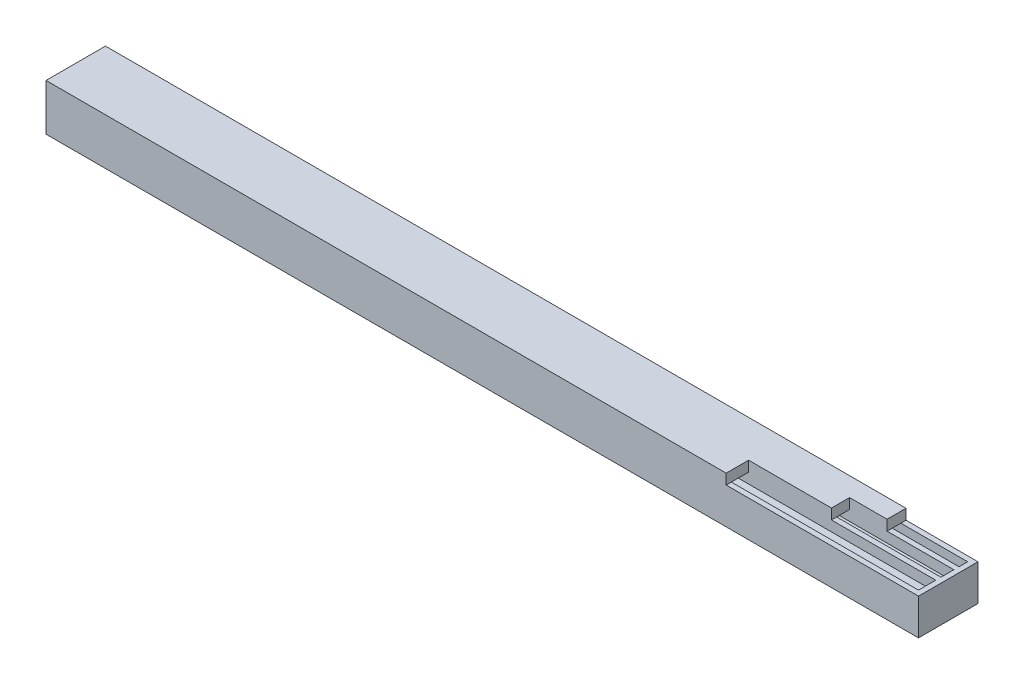
SolidWorks part; units mm, degrees
ref_plane "Front Plane" through (0, 0, 0) normal (0, 0, 1) x (1, 0, 0)
ref_plane "Top Plane" through (0, 0, 0) normal (0, 1, 0) x (1, 0, 0)
ref_plane "Right Plane" through (0, 0, 0) normal (1, 0, 0) x (0, 0, -1)
sketch "Sketch1" plane through (0, 0, 0) normal (0, 1, 0) x (1, 0, 0)
  line L1 (0, 0) -> (500, 0) construction
  line L2 (0, 0) -> (0, 5) construction
  line L3 (0, 5) -> (500, 5) construction
  line L4 (500, 0) -> (500, 5) construction
  line L5 (0, -3) -> (500, -3) construction
  line L6 (0, -3) -> (0, -10.5) construction
  line L7 (0, -10.5) -> (500, -10.5) construction
  line L8 (500, -3) -> (500, -10.5) construction
  line L9 (0, -13.5) -> (500, -13.5) construction
  line L10 (0, -13.5) -> (0, -23.5) construction
  line L11 (0, -23.5) -> (500, -23.5) construction
  line L12 (500, -13.5) -> (500, -23.5) construction
  line L13 (-3, -26.5) -> (503, -26.5)
  line L14 (-3, -26.5) -> (-3, 8)
  line L15 (-3, 8) -> (503, 8)
  line L16 (503, -26.5) -> (503, 8)
  dimension "D1" = 5
  dimension "D2" = 7.5
  dimension "D3" = 3
  dimension "D4" = 3
  dimension "D5" = 10
  dimension "D6" = 500
  dimension "D7" = 3
  dimension "D8" = 3
  dimension "D9" = 3
  dimension "D10" = 3
extrude "Boss-Extrude1" add sketch "Sketch1" against normal blind 15
sketch "Sketch3" plane through (0, 0, 0) normal (0, 1, 0) x (1, 0, 0)
  line L1 (0, -13.5) -> (500, -13.5)
  line L2 (0, -13.5) -> (0, -23.5)
  line L3 (0, -23.5) -> (500, -23.5)
  line L4 (500, -13.5) -> (500, -23.5)
  line L5 (0, 5) -> (500, 5)
  line L6 (0, 5) -> (0, 0)
  line L7 (0, 0) -> (500, 0)
  line L8 (500, 5) -> (500, 0)
  line L9 (500, -3) -> (0, -3)
  line L10 (500, -3) -> (500, -10.5)
  line L11 (500, -10.5) -> (0, -10.5)
  line L12 (0, -3) -> (0, -10.5)
  line L13 (-3, 8) -> (503, 8)
  line L14 (-3, 8) -> (-3, -26.5)
  line L15 (-3, -26.5) -> (503, -26.5)
  line L16 (503, 8) -> (503, -26.5)
extrude "Boss-Extrude2" add sketch "Sketch3" along normal blind 6
sketch "Sketch4" plane through (0, 6, 0) normal (0, 1, 0) x (1, 0, 0)
  line L0 (461.2649, 8) -> (461.2649, -3)
  line L1 (503, 8) -> (-3, 8) construction
  line L2 (500, -3) -> (0, -3) construction
  line L3 (461.2649, -3) -> (439.5156, -3)
  line L4 (439.5156, -3) -> (439.5156, -13.5)
  line L5 (500, -13.5) -> (0, -13.5) construction
  line L6 (439.5156, -13.5) -> (391.4566, -13.5)
  line L7 (391.4566, -13.5) -> (391.4566, -26.5)
  line L8 (-3, -26.5) -> (503, -26.5) construction
  line L9 (391.4566, -26.5) -> (-3, -26.5)
  line L10 (-3, -26.5) -> (-3, 8)
  line L11 (-3, 8) -> (461.2649, 8)
extrude "Boss-Extrude3" add sketch "Sketch4" along normal blind 6
